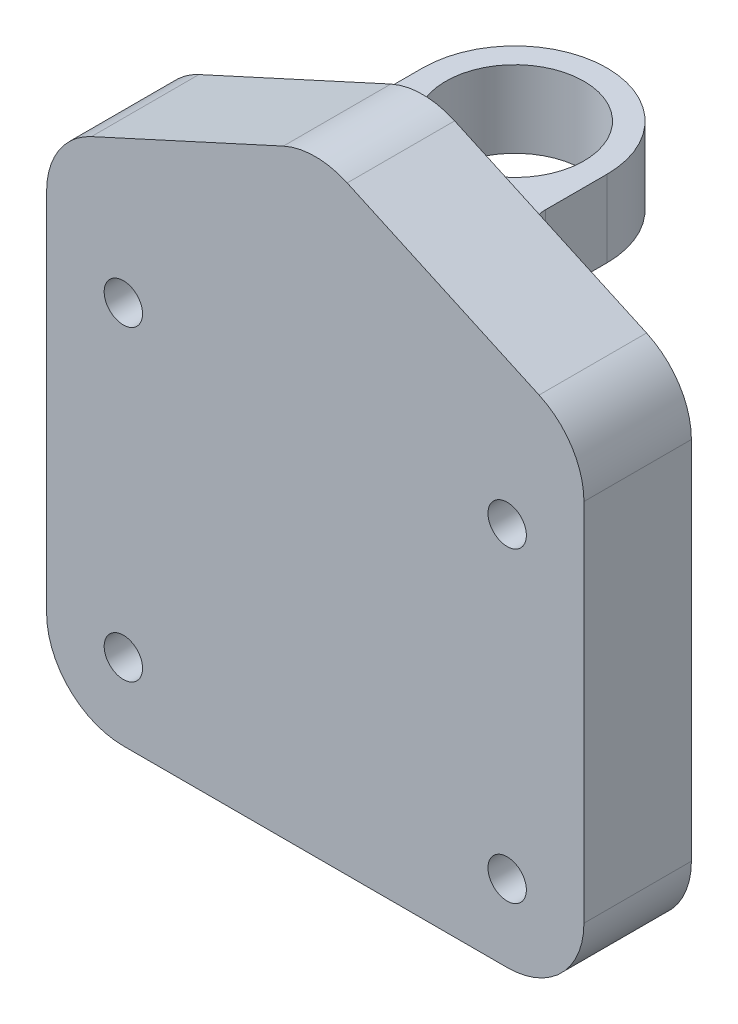
SolidWorks part; units mm, degrees
material "ABS"
ref_plane "Front Plane" through (0, 0, 0) normal (0, 0, 1) x (1, 0, 0)
ref_plane "Top Plane" through (0, 0, 0) normal (0, 1, 0) x (1, 0, 0)
ref_plane "Right Plane" through (0, 0, 0) normal (1, 0, 0) x (0, 0, -1)
sketch "Sketch1" plane through (0, -692.7323, 224.6348) normal (0, 0, -1) x (1, 0, 0)
  line L0 (17.5, -2.4767) -> (17.5, -34.4767)
  line L1 (12.5, -7.4767) -> (-12.5, -7.4767) construction
  line L4 (-12.5, -7.4767) -> (-12.5, -27.4767) construction
  line L6 (-17.5, -2.4767) -> (-17.5, -34.4767)
  line L7 (17.5, -2.4767) -> (-17.5, -2.4767)
  line L8 (17.5, -34.4767) -> (0, -42.4767)
  line L9 (0, -42.4767) -> (-17.5, -34.4767)
  line L10 (0, -2.4767) -> (0, -70.9197) construction
  circle A0 centre (-12.5, -27.4767) radius 1.25 construction
  circle A1 centre (12.5, -27.4767) radius 1.25 construction
  circle A2 centre (12.5, -7.4767) radius 1.25 construction
  circle A3 centre (-12.5, -7.4767) radius 1.25 construction
  circle A4 centre (-12.5, -27.4767) radius 1.25
  circle A5 centre (12.5, -27.4767) radius 1.25
  circle A6 centre (12.5, -7.4767) radius 1.25
  circle A7 centre (-12.5, -7.4767) radius 1.25
  dimension "D1" = 35
  dimension "D2" = 40
  dimension "D3" = 32
extrude "Boss-Extrude1" add sketch "Sketch1" along normal blind 7
ref_plane "Plane1" through (0, -685.2556, 0) normal (0, -1, 0) x (1, 0, 0)
ref_plane "Plane2" through (0, -655.2556, 0) normal (0, -1, 0) x (1, 0, 0)
sketch "Sketch2" plane through (0, -655.2556, 0) normal (0, -1, 0) x (1, 0, 0)
  line L0 (17.5, 217.6348) -> (-17.5, 217.6348) construction
  line L1 (6, 217.6348) -> (-6, 217.6348)
  line L2 (6, 217.6348) -> (6, 211.6348)
  line L3 (0, -10) -> (0, -25.0866) construction
  line L4 (-6, 217.6348) -> (-6, 211.6348)
  arc A0 (-6, 211.6348) -> (6, 211.6348) centre (0, 211.6348) ccw
  circle A1 centre (0, 211.6348) radius 4.5
  point P10 (0, 217.6348)
  dimension "D1" = 12
  dimension "D5" = 9
  dimension "D2" = 6
  dimension "D3" = 6
  dimension "D4" = 6
extrude "Boss-Extrude2" add sketch "Sketch2" along normal blind 5
sketch "Sketch3" plane through (0, -685.2556, 0) normal (0, -1, 0) x (1, 0, 0)
  line L3 (6, 217.6348) -> (-6, 217.6348)
  line L4 (-6, 217.6348) -> (-6, 211.6348)
  line L5 (6, 211.6348) -> (6, 217.6348)
  line L6 (6, 217.6348) -> (-6, 217.6348)
  line L7 (-6, 217.6348) -> (-6, 211.6348)
  line L8 (6, 211.6348) -> (6, 217.6348)
  circle A1 centre (0, 211.6348) radius 4.5
  circle A2 centre (0, 211.6348) radius 4.5
  arc A3 (-6, 211.6348) -> (6, 211.6348) centre (0, 211.6348) ccw
  arc A4 (-6, 211.6348) -> (6, 211.6348) centre (0, 211.6348) ccw
  dimension "D1" = 0
  dimension "D2" = 0
extrude "Boss-Extrude3" add sketch "Sketch3" along normal blind 5
fillet "Fillet1" radius 2 4 edges at (-6, -657.7556, 217.6348) (6, -657.7556, 217.6348) (6, -687.7556, 217.6348) (-6, -687.7556, 217.6348)
fillet "Fillet2" radius 5 5 edges at (-17.5, -690.2556, 221.1348) (17.5, -690.2556, 221.1348) (17.5, -658.2556, 221.1348) (0, -650.2556, 221.1348) (-17.5, -658.2556, 221.1348)
